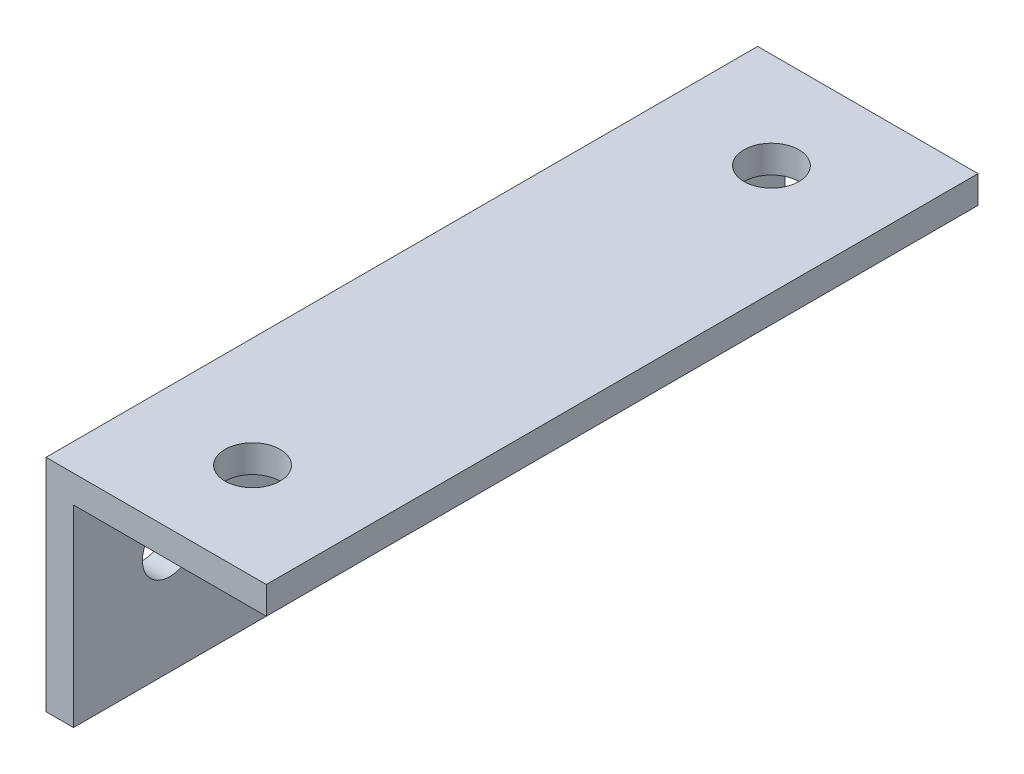
SolidWorks part; units mm, degrees
ref_plane "Front Plane" through (0, 0, 0) normal (0, 0, 1) x (1, 0, 0)
ref_plane "Top Plane" through (0, 0, 0) normal (0, 1, 0) x (1, 0, 0)
ref_plane "Right Plane" through (0, 0, 0) normal (1, 0, 0) x (0, 0, -1)
sketch "Sketch1" plane through (0, 0, 0) normal (0, 0, 1) x (1, 0, 0)
  line L0 (0, 0) -> (0, 25.4)
  line L1 (0, 25.4) -> (25.4, 25.4)
  line L2 (3.175, 0) -> (3.175, 22.225)
  line L3 (3.175, 22.225) -> (25.4, 22.225)
  line L4 (3.175, 0) -> (0, 0)
  line L5 (25.4, 22.225) -> (25.4, 25.4)
  dimension "D1" = 25.4
  dimension "D2" = 25.4
  dimension "D3" = 3.175
extrude "Boss-Extrude1" add sketch "Sketch1" along normal blind 82.042
sketch "Sketch2" plane through (0, 0, 0) normal (-1, 0, 0) x (0, 0, 1)
  circle A0 centre (70.9295, 12.7) radius 3.175
  circle A1 centre (11.1125, 12.7) radius 3.175
  dimension "D2" = 6.35
extrude "Cut-Extrude2" cut sketch "Sketch2" against normal blind 82.042
sketch "Sketch3" plane through (0, 25.4, 0) normal (0, 1, 0) x (1, 0, 0)
  circle A0 centre (12.7, -11.1125) radius 3.175
  circle A1 centre (12.7, -70.9295) radius 3.175
  dimension "D2" = 6.35
extrude "Cut-Extrude3" cut sketch "Sketch3" against normal blind 82.042
